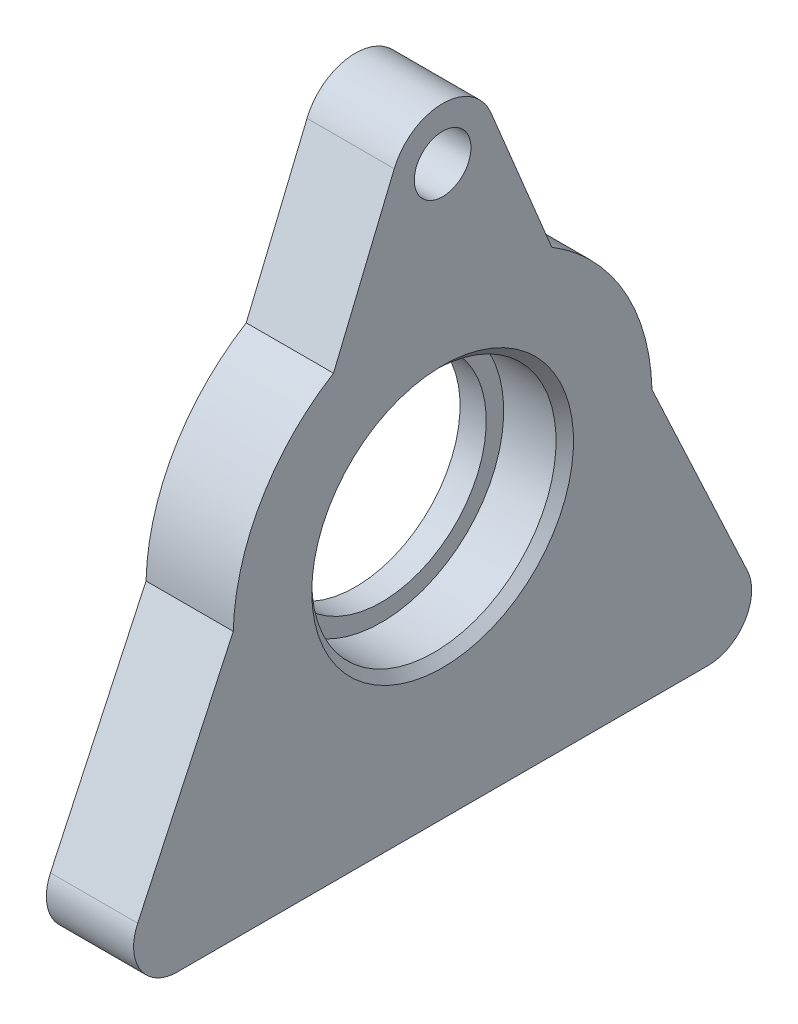
SolidWorks part; units mm, degrees
material "3.0205 (EN-AW 1200)"
ref_plane "Спереди" through (0, 0, 0) normal (0, 0, 1) x (1, 0, 0)
ref_plane "Сверху" through (0, 0, 0) normal (0, 1, 0) x (1, 0, 0)
ref_plane "Справа" through (0, 0, 0) normal (1, 0, 0) x (0, 0, -1)
sketch "Эскиз1" plane through (0, 0, 0) normal (0, 0, 1) x (1, 0, 0)
  line L0 (0, 14) -> (0, 24)
  line L1 (0, 24) -> (10, 24)
  line L2 (10, 24) -> (10, 14)
  line L3 (10, 14) -> (0, 14)
  line L4 (-29.3651, 0) -> (90.6978, 0) construction
  dimension "D1" = 28
  dimension "D2" = 10
  dimension "D3" = 10
revolve "Повернуть1" add sketch "Эскиз1" angle 360 about L4
sketch "Эскиз6" plane through (0, 0, 0) normal (-1, 0, 0) x (0, 0, 1)
  circle A0 centre (0, 0) radius 14
  circle A1 centre (0, 0) radius 12
  dimension "D1" = 28
  dimension "D2" = 24
extrude "Бобышка-Вытянуть1" add sketch "Эскиз6" against normal blind 3
sketch "Эскиз7" plane through (0, 0, 0) normal (-1, 0, 0) x (0, 0, 1)
  line L0 (-30.4151, -30) -> (30.4151, -30)
  line L1 (0, 0) -> (0, -67.0529) construction
  line L2 (-34.9467, -22.8869) -> (-19.9388, 9.2976)
  line L3 (34.9467, -22.8869) -> (19.9388, 9.2976)
  arc A0 (19.9388, 9.2976) -> (-19.9388, 9.2976) centre (0, 0) ccw
  circle A1 centre (0, 0) radius 28 construction
  circle A2 centre (0, 0) radius 19.5
  arc A3 (30.4151, -30) -> (34.9467, -22.8869) centre (30.4151, -25) ccw
  arc A4 (-30.4151, -30) -> (-34.9467, -22.8869) centre (-30.4151, -25) cw
  point P11 (38.2635, -30)
  point P14 (-38.2635, -30)
  dimension "D1" = 44
  dimension "D2" = 56
  dimension "D5" = 39
  dimension "D6" = 5
  dimension "D3" = 30
  dimension "D4" = 50
extrude "Бобышка-Вытянуть2" add sketch "Эскиз7" against normal up to surface (10 mm away) up to face at (10, 0, 24)
hole_wizard "Отверстие обработанное метчиком M43" positions "Эскиз8" profile "Эскиз9" tap size "M4" standard "DIN"
sketch "Эскиз8" plane through (0, -30, 0) normal (0, -1, 0) x (-1, 0, 0)
  line L0 (-5, 30.4151) -> (-5, -49.5848) construction
  line L1 (-10, 30.4151) -> (0, 30.4151) construction
  line L2 (-30.6259, 0) -> (48.7419, 0) construction
  point P18 (-5, 25)
  point P22 (-5, -25)
  point P27 (-5, 0)
  dimension "D1" = 25
sketch "Эскиз9" plane through (5, -30, 0) normal (1, 0, 0) x (0, 0, -1)
  line L0 (0, 0) -> (0, 12.9914)
  line L1 (0, 12.9914) -> (1.65, 12)
  line L2 (1.65, 12) -> (1.65, 0.85)
  line L3 (1.65, 0.85) -> (2.5, 0)
  line L5 (2.5, 0) -> (0, 0)
  line L6 (-1.65, 0.85) -> (-2.5, 0) construction
  line L10 (0, 12.9914) -> (-1.65, 12) construction
  line L11 (0, -6.35) -> (0, 107.95) construction
  dimension "Диаметр сверла" = 3.3
  dimension "Глубина сверла" = 12
  dimension "Диаметр передней зенковки" = 5
  dimension "Угол передней зенковки" = 90
  dimension "Угол заточки сверла" = 118
cosmetic thread "Отверстие резьбы11" parameters "D1"=10, "D2"=4
cosmetic thread "Отверстие резьбы12" parameters "D1"=10, "D2"=4
cosmetic thread "Отверстие резьбы13" parameters "D1"=10, "D2"=4
sketch "Эскиз10" plane through (0, 0, 0) normal (-1, 0, 0) x (0, 0, 1)
  line L0 (0, 0) -> (0, 50000) construction
  line L1 (-12.5074, 20.4833) -> (-5.5433, 37.2961)
  line L2 (12.5074, 20.4833) -> (5.5433, 37.2961)
  arc A0 (5.5433, 37.2961) -> (-5.5433, 37.2961) centre (0, 35) ccw
  arc A1 (23.9924, 0.6046) -> (-23.9924, 0.6046) centre (0, 0) ccw construction
  arc A2 (12.5074, 20.4833) -> (-12.5074, 20.4833) centre (0, 0) ccw
  dimension "D1" = 12
  dimension "D2" = 35
  dimension "D3" = 45
extrude "Бобышка-Вытянуть3" add sketch "Эскиз10" against normal blind 10
sketch "Эскиз13" plane through (0, 0, 0) normal (-1, 0, 0) x (0, 0, 1)
  point P0 (0, 35)
hole_wizard "Сверло под метчик  спиральное M61" positions "Эскиз13" profile "Эскиз12" hole size "M6x1.0" standard "DIN" end condition through all
sketch "Эскиз12" plane through (0, 35, 0) normal (0, 1, 0) x (0, 0, 1)
  line L0 (0, 0) -> (0, 10)
  line L1 (0, 10) -> (3.25, 10)
  line L2 (3.25, 10) -> (3.25, 0)
  line L5 (3.25, 0) -> (0, 0)
  line L11 (0, -6.35) -> (0, 107.95) construction
  dimension "Диаметр сквозного отверстия" = 6.5
  dimension "Глубина сквозного отверстия" = 10
chamfer "Фаска1" distance 1 angle 45 1 edges at (10, 0, 14)
